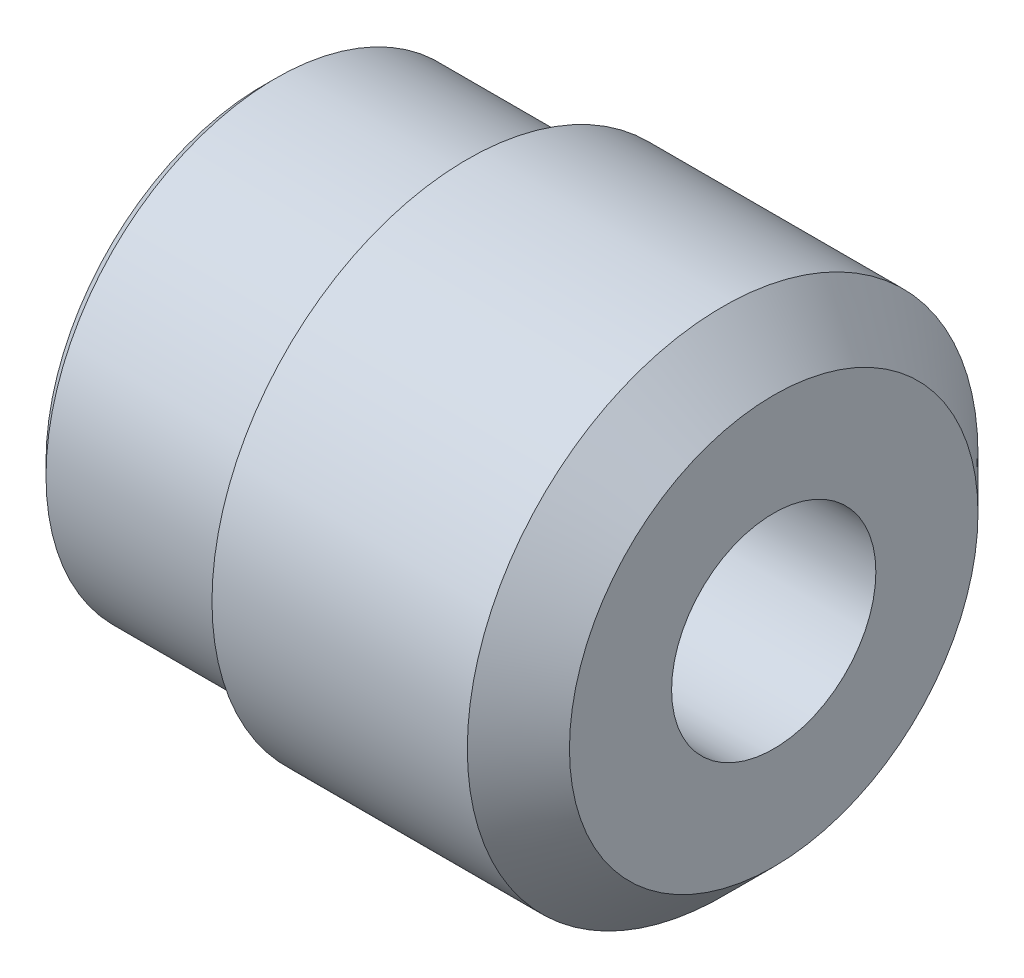
SolidWorks part; units mm, degrees
ref_plane "Plan1" through (0, 0, 0) normal (0, 0, 1) x (1, 0, 0)
ref_plane "Plan2" through (0, 0, 0) normal (0, 1, 0) x (1, 0, 0)
ref_plane "Plan3" through (0, 0, 0) normal (1, 0, 0) x (0, 0, -1)
sketch "Esquisse1" plane through (0, 0, 0) normal (0, 0, 1) x (1, 0, 0)
  line L0 (0, 6) -> (0, 9)
  line L1 (0, 9) -> (8, 9)
  line L2 (8, 9) -> (8, 10)
  line L3 (8, 10) -> (20, 10)
  line L4 (20, 10) -> (20, 4)
  line L5 (0, 6) -> (14, 6)
  line L6 (14, 6) -> (14, 4)
  line L7 (14, 4) -> (20, 4)
  line L8 (0, 0) -> (22, 0) construction
  dimension "D2" = 8
  dimension "D3" = 1
  dimension "D4" = 12
revolve "Base-Révolution" add sketch "Esquisse1" angle 360 about L8
chamfer "Chanfrein1" distance 2 angle 45
chamfer "Chanfrein2" distance 0.5 angle 45
